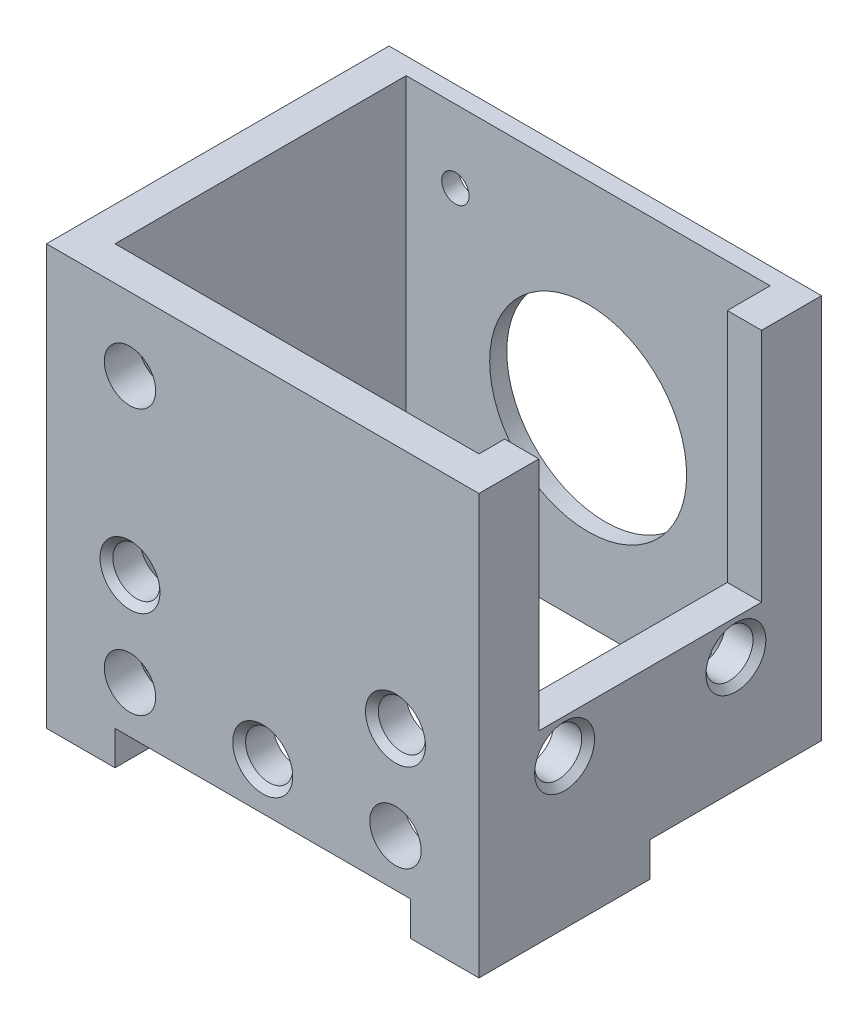
SolidWorks part; units mm, degrees
material "PET"
ref_plane "Front Plane" through (0, 0, 0) normal (0, 0, 1) x (1, 0, 0)
ref_plane "Top Plane" through (0, 0, 0) normal (0, 1, 0) x (1, 0, 0)
ref_plane "Right Plane" through (0, 0, 0) normal (1, 0, 0) x (0, 0, -1)
sketch "Sketch2" plane through (0, 0, 0) normal (0, 1, 0) x (1, 0, 0)
  line L1 (21.25, 17) -> (-21.25, 17)
  line L2 (21.25, 17) -> (21.25, -17)
  line L3 (21.25, -17) -> (-21.25, -17)
  line L4 (-21.25, 17) -> (-21.25, -17)
  line L5 (21.25, 17) -> (-21.25, -17) construction
  line L6 (21.25, -17) -> (-21.25, 17) construction
  line L7 (-25.25, 19) -> (25.25, 19)
  line L8 (-25.25, 19) -> (-25.25, -21)
  line L9 (-25.25, -21) -> (25.25, -21)
  line L10 (25.25, 19) -> (25.25, -21)
  point P1 (0, 0)
  dimension "D1" = 42.5
  dimension "D2" = 34
  dimension "D3" = 4
  dimension "D4" = 4
  dimension "D5" = 4
  dimension "D6" = 2
extrude "Boss-Extrude1" add sketch "Sketch2" along normal blind 45
sketch "Sketch3" plane through (25.25, 0, 0) normal (1, 0, 0) x (0, 0, -1)
  line L0 (-21, 45) -> (19, 45) construction
  line L1 (-14, 45) -> (12, 45)
  line L2 (-14, 45) -> (-14, 17.5)
  line L3 (-14, 17.5) -> (12, 17.5)
  line L4 (12, 45) -> (12, 17.5)
  line L5 (19, 45) -> (19, 0) construction
  line L6 (-21, 45) -> (-21, 0) construction
  line L7 (-21, 0) -> (19, 0) construction
  dimension "D1" = 7
  dimension "D2" = 7
  dimension "D3" = 17.5
extrude "Cut-Extrude1" cut sketch "Sketch3" against normal up to next
sketch "Sketch4" plane through (0, 0, -19) normal (0, 0, -1) x (-1, 0, 0)
  line L0 (-25.25, 0) -> (25.25, 0) construction
  line L1 (0, 0) -> (0, 21) construction
  line L3 (15.5, 36.5) -> (-15.5, 36.5) construction
  line L4 (15.5, 36.5) -> (15.5, 5.5) construction
  line L5 (15.5, 5.5) -> (-15.5, 5.5) construction
  line L6 (-15.5, 36.5) -> (-15.5, 5.5) construction
  line L7 (15.5, 36.5) -> (-15.5, 5.5) construction
  line L8 (15.5, 5.5) -> (-15.5, 36.5) construction
  circle A0 centre (0, 21) radius 11.5
  circle A1 centre (-15.5, 5.5) radius 1.6
  circle A2 centre (15.5, 5.5) radius 1.6
  circle A3 centre (15.5, 36.5) radius 1.6
  dimension "D1" = 21
  dimension "D2" = 23
  dimension "D5" = 3.2
  dimension "D6" = 3.2
  dimension "D7" = 3.2
  dimension "D3" = 31
  dimension "D4" = 31
extrude "Cut-Extrude2" cut sketch "Sketch4" against normal up to next
sketch "Sketch5" plane through (0, 0, 21) normal (0, 0, 1) x (1, 0, 0)
  circle A0 centre (-15.5, 36.5) radius 3
  circle A1 centre (-15.5, 5.5) radius 3
  circle A2 centre (15.5, 5.5) radius 3
  dimension "D1" = 6
  dimension "D2" = 6
  dimension "D3" = 6
extrude "Cut-Extrude3" cut sketch "Sketch5" against normal up to next
sketch "Sketch6" plane through (0, 0, 21) normal (0, 0, 1) x (1, 0, 0)
  line L0 (-15.5, 5.5) -> (-15.5, 27.2301) construction
  line L1 (15.5, 5.5) -> (15.5, 27.2301) construction
  circle A0 centre (-15.5, 16.3651) radius 2.75
  circle A1 centre (0, 5.5) radius 2.75
  circle A2 centre (15.5, 16.3651) radius 2.75
  dimension "D1" = 5.5
  dimension "D2" = 5.5
  dimension "D3" = 5.5
extrude "Cut-Extrude4" cut sketch "Sketch6" against normal up to next
sketch "Sketch7" plane through (25.25, 0, 0) normal (1, 0, 0) x (0, 0, -1)
  line L0 (-11, 13.4406) -> (9, 13.4406) construction
  line L1 (-21, 45) -> (-21, 0) construction
  line L2 (-14, 17.5) -> (12, 17.5) construction
  circle A0 centre (-11, 13.4406) radius 2.75
  circle A1 centre (9, 13.4406) radius 2.75
  dimension "D1" = 5.5
  dimension "D2" = 5.5
  dimension "D3" = 10
  dimension "D4" = 4.0594
  dimension "D5" = 20
extrude "Cut-Extrude5" cut sketch "Sketch7" against normal through all
sketch "Sketch8" plane through (0, 0, 0) normal (0, -1, 0) x (1, 0, 0)
  line L0 (19, 1) -> (17.25, 11)
  line L1 (-25.25, 21) -> (-17.25, 21)
  line L2 (-25.25, 21) -> (-25.25, -4)
  line L3 (-25.25, -4) -> (-17.25, -4)
  line L4 (-17.25, 21) -> (-17.25, -4)
  line L5 (25.25, 21) -> (17.25, 21)
  line L6 (25.25, 21) -> (25.25, 1)
  line L7 (25.25, 1) -> (19, 1)
  line L8 (17.25, 21) -> (17.25, 11)
  dimension "D1" = 20
  dimension "D2" = 8
  dimension "D3" = 8
  dimension "D4" = 25
  dimension "D5" = 1.75
  dimension "D6" = 10
extrude "Boss-Extrude2" add sketch "Sketch8" along normal blind 4
sketch "Sketch9" plane through (0, -4, 0) normal (0, -1, 0) x (1, 0, 0)
  line L0 (-21.25, 21) -> (-21.25, -4) construction
  line L1 (-17.25, 21) -> (-25.25, 21) construction
  line L2 (-25.25, -4) -> (-17.25, -4) construction
  line L3 (21.25, 21) -> (21.25, 1) construction
  line L4 (25.25, 21) -> (17.25, 21) construction
  line L5 (19, 1) -> (25.25, 1) construction
  circle A0 centre (-21.25, 13) radius 2.25
  circle A1 centre (-21.25, 0.5) radius 2.25
  circle A2 centre (21.25, 6) radius 2.25
  circle A3 centre (21.25, 16) radius 2.25
  dimension "D1" = 4.5
  dimension "D2" = 4.5
  dimension "D3" = 4.5
  dimension "D4" = 8
  dimension "D5" = 5
  dimension "D6" = 5
  dimension "D7" = 4.5
  dimension "D8" = 4.5
extrude "Cut-Extrude6" cut sketch "Sketch9" against normal up to surface (4 mm away) up to face at (-19.25, 0, 6.5)
chamfer "Chamfer1" distance 0.75 angle 45 11 edges at (18.25, 16.3651, 21) (2.75, 5.5, 21) (-12.75, 16.3651, 21) (-25.25, 13.4406, -11.75) (-25.25, 13.4406, 8.25) (-21.25, -4, 10.75) (21.25, -4, 13.75) (21.25, -4, 3.75) (-21.25, -4, -1.75) (25.25, 13.4406, -11.75) (25.25, 13.4406, 8.25)
